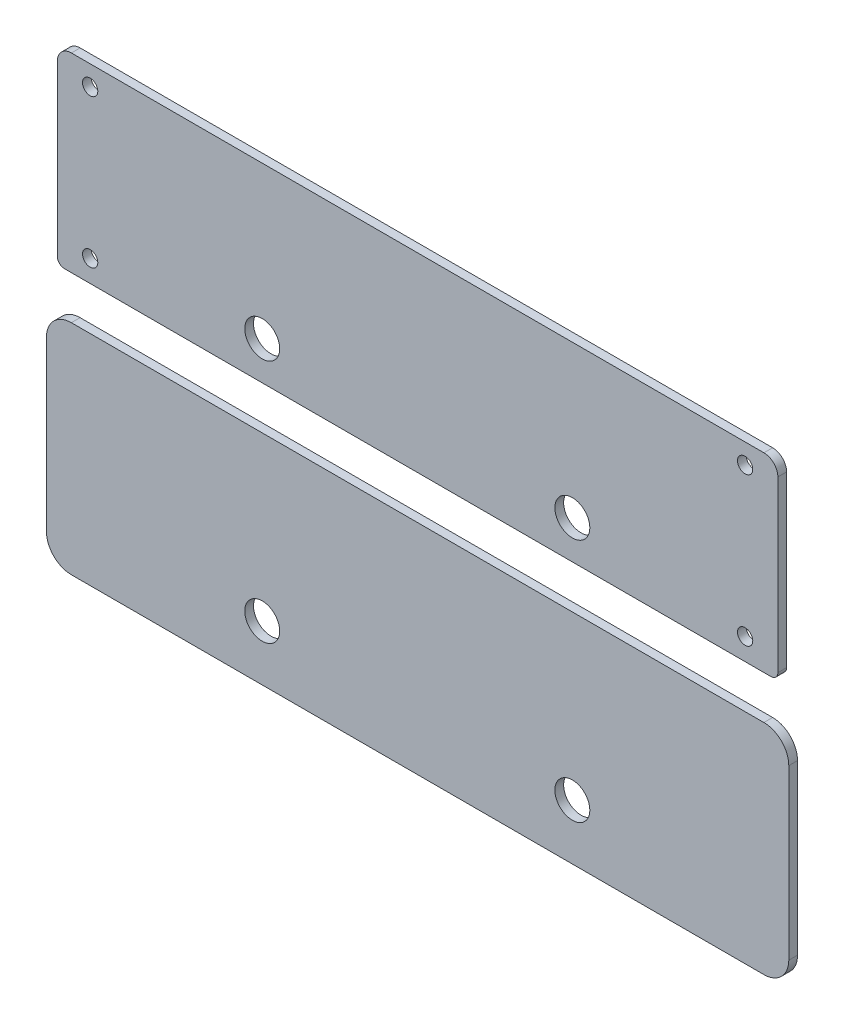
SolidWorks part; units mm, degrees
ref_plane "Front" through (0, 0, 0) normal (0, 0, 1) x (1, 0, 0)
ref_plane "Top" through (0, 0, 0) normal (0, 1, 0) x (1, 0, 0)
ref_plane "Right" through (0, 0, 0) normal (1, 0, 0) x (0, 0, -1)
sketch "Sketch1" plane through (0, 0, 0) normal (0, 0, 1) x (1, 0, 0)
  line L0 (-52.6295, -31.75) -> (-37.7705, -31.75)
  line L1 (37.5705, -31.75) -> (52.4295, -31.75)
  line L2 (-107.95, 24.511) -> (-107.95, -24.511)
  line L3 (-100.711, -31.75) -> (-52.6295, -31.75)
  line L4 (-37.7705, -31.75) -> (37.5705, -31.75)
  line L5 (52.4295, -31.75) -> (100.711, -31.75)
  line L6 (107.95, -24.511) -> (107.95, 24.511)
  line L7 (100.711, 31.75) -> (-100.711, 31.75)
  line L24 (100.711, 99.695) -> (-100.711, 99.695)
  line L25 (-104.775, 95.631) -> (-104.775, 50.345)
  line L31 (104.775, 50.345) -> (104.775, 95.631)
  line L32 (107.95, 46.609) -> (107.95, 95.631) [skipped]
  line L33 (84.775, 44.345) -> (-84.775, 44.345)
  line L34 (100.711, 102.87) -> (-100.711, 102.87) [skipped]
  line L35 (84.775, 44.345) -> (84.775, 50.345)
  line L36 (52.4295, 39.37) -> (100.711, 39.37) [skipped]
  line L37 (84.775, 50.345) -> (104.775, 50.345)
  line L38 (37.5705, 39.37) -> (52.4295, 39.37) [skipped]
  line L40 (-37.7705, 39.37) -> (37.5705, 39.37) [skipped]
  line L41 (0, 99.695) -> (0, 44.345) construction
  line L42 (-52.6295, 39.37) -> (-37.7705, 39.37) [skipped]
  line L43 (-84.775, 50.345) -> (-104.775, 50.345)
  line L44 (-100.711, 39.37) -> (-52.6295, 39.37) [skipped]
  line L45 (-84.775, 44.345) -> (-84.775, 50.345)
  line L46 (-107.95, 95.631) -> (-107.95, 46.609) [skipped]
  circle A0 centre (-45.2, -15.6502) radius 5.08
  circle A1 centre (45, -15.6502) radius 5.08
  arc A2 (-100.711, 31.75) -> (-107.95, 24.511) centre (-100.711, 24.511) ccw
  arc A3 (-107.95, -24.511) -> (-100.711, -31.75) centre (-100.711, -24.511) ccw
  arc A4 (100.711, -31.75) -> (107.95, -24.511) centre (100.711, -24.511) ccw
  arc A5 (107.95, 24.511) -> (100.711, 31.75) centre (100.711, 24.511) ccw
  circle A10 centre (-45.2, 55.4698) radius 5.08
  circle A11 centre (45, 55.4698) radius 5.08
  arc A18 (-100.711, 99.695) -> (-104.775, 95.631) centre (-100.711, 95.631) ccw
  arc A21 (104.775, 95.631) -> (100.711, 99.695) centre (100.711, 95.631) ccw
  arc A24 (107.95, 95.631) -> (100.711, 102.87) centre (100.711, 95.631) ccw [skipped]
  circle A25 centre (66.273, 2.3) radius 1.905 construction
  arc A26 (100.711, 39.37) -> (107.95, 46.609) centre (100.711, 46.609) ccw [skipped]
  arc A28 (-107.95, 46.609) -> (-100.711, 39.37) centre (-100.711, 46.609) ccw [skipped]
  circle A29 centre (35.023, 2.3) radius 1.905 construction
  arc A30 (-100.711, 102.87) -> (-107.95, 95.631) centre (-100.711, 95.631) ccw [skipped]
  circle A32 centre (50.648, 2.3) radius 12.065 construction
  circle A34 centre (12.5, 2.3) radius 9.25 construction
  dimension "D3" = 2
extrude "Boss-Extrude1" add sketch "Sketch1" along normal blind 2.54
sketch "Sketch2" [suppressed] plane through (0, 0, 2.54) normal (0, 0, 1) x (1, 0, 0)
  line L0 (-20.0864, 22.2366) -> (3.9841, 22.2366)
  line L1 (3.9841, 22.2366) -> (3.9841, 4.3544)
  line L2 (3.9841, 4.3544) -> (21.8236, 4.3544)
  line L3 (21.8236, 4.3544) -> (21.8236, -19.7588)
  line L4 (21.8236, -19.7588) -> (15.806, -19.7588)
  line L5 (15.806, -19.7588) -> (15.806, -1.7486)
  line L6 (15.806, -1.7486) -> (-1.9908, -1.7486)
  line L7 (-1.9908, -1.7486) -> (-1.9908, 16.2189)
  line L8 (-1.9908, 16.2189) -> (-20.0864, 16.2189)
  line L9 (-20.0864, 16.2189) -> (-20.0864, 22.2366)
  line L10 (-20.0864, 4.3544) -> (-14.0261, 4.3544)
  line L11 (-14.0261, 4.3544) -> (-14.0261, -13.6985)
  line L12 (-14.0261, -13.6985) -> (3.9841, -13.6985)
  line L13 (3.9841, -13.6985) -> (3.9841, -19.7588)
  line L14 (3.9841, -19.7588) -> (-20.0864, -19.7588)
  line L15 (-20.0864, -19.7588) -> (-20.0864, 4.3544)
extrude "Cut-Extrude1" [suppressed] cut sketch "Sketch2" against normal through all
sketch "Sketch3" [suppressed] plane through (0, 0, 2.54) normal (0, 0, 1) x (1, 0, 0)
  circle A0 centre (-45.2, 55.4698) radius 5.08 construction
  circle A1 centre (-45.2, 55.4698) radius 5.08
  circle A2 centre (45, 55.4698) radius 5.08 construction
  circle A3 centre (45, 55.4698) radius 5.08
extrude "Boss-Extrude2" [suppressed] add sketch "Sketch3" against normal through all
sketch "Sketch5" [suppressed] plane through (0, 0, 2.54) normal (0, 0, 1) x (1, 0, 0)
  line L0 (3.9841, -19.7588) -> (3.9841, -13.6985) construction
  line L1 (-20.0864, -19.7588) -> (3.9841, -19.7588) construction
  line L2 (-20.0864, 4.3544) -> (-20.0864, -19.7588) construction
  line L3 (-14.0261, 4.3544) -> (-20.0864, 4.3544) construction
  line L4 (-14.0261, -13.6985) -> (-14.0261, 4.3544) construction
  line L5 (3.9841, -13.6985) -> (-14.0261, -13.6985) construction
  line L6 (3.9841, -19.7588) -> (3.9841, -13.6985)
  line L7 (-20.0864, -19.7588) -> (3.9841, -19.7588)
  line L8 (-20.0864, 4.3544) -> (-20.0864, -19.7588)
  line L9 (-14.0261, 4.3544) -> (-20.0864, 4.3544)
  line L10 (-14.0261, -13.6985) -> (-14.0261, 4.3544)
  line L11 (3.9841, -13.6985) -> (-14.0261, -13.6985)
  line L12 (-1.9908, -1.7486) -> (15.806, -1.7486) construction
  line L13 (-1.9908, 16.2189) -> (-1.9908, -1.7486) construction
  line L14 (-20.0864, 16.2189) -> (-1.9908, 16.2189) construction
  line L15 (-20.0864, 22.2366) -> (-20.0864, 16.2189) construction
  line L16 (3.9841, 22.2366) -> (-20.0864, 22.2366) construction
  line L17 (3.9841, 4.3544) -> (3.9841, 22.2366) construction
  line L18 (21.8236, 4.3544) -> (3.9841, 4.3544) construction
  line L19 (21.8236, -19.7588) -> (21.8236, 4.3544) construction
  line L20 (15.806, -19.7588) -> (21.8236, -19.7588) construction
  line L21 (15.806, -1.7486) -> (15.806, -19.7588) construction
  line L22 (-1.9908, -1.7486) -> (15.806, -1.7486)
  line L23 (-1.9908, 16.2189) -> (-1.9908, -1.7486)
  line L24 (-20.0864, 16.2189) -> (-1.9908, 16.2189)
  line L25 (-20.0864, 22.2366) -> (-20.0864, 16.2189)
  line L26 (3.9841, 22.2366) -> (-20.0864, 22.2366)
  line L27 (3.9841, 4.3544) -> (3.9841, 22.2366)
  line L28 (21.8236, 4.3544) -> (3.9841, 4.3544)
  line L29 (21.8236, -19.7588) -> (21.8236, 4.3544)
  line L30 (15.806, -19.7588) -> (21.8236, -19.7588)
  line L31 (15.806, -1.7486) -> (15.806, -19.7588)
  circle A0 centre (-45.2, -15.6502) radius 5.08 construction
  circle A1 centre (-45.2, -15.6502) radius 5.08
  circle A2 centre (45, -15.6502) radius 5.08 construction
  circle A3 centre (45, -15.6502) radius 5.08
extrude "Boss-Extrude3" [suppressed] add sketch "Sketch5" against normal through all
sketch "Sketch6" [suppressed] plane through (0, 0, 2.54) normal (0, 0, 1) x (1, 0, 0)
  circle A0 centre (12.5, 2.3) radius 9.25 construction
  circle A1 centre (12.5, 2.3) radius 9.25
  circle A2 centre (35.023, 2.3) radius 1.905 construction
  circle A3 centre (35.023, 2.3) radius 1.905
  circle A4 centre (50.648, 2.3) radius 12.065 construction
  circle A5 centre (50.648, 2.3) radius 12.065
  circle A6 centre (66.273, 2.3) radius 1.905 construction
  circle A7 centre (66.273, 2.3) radius 1.905
extrude "Cut-Extrude2" [suppressed] cut sketch "Sketch6" against normal through all
sketch "Sketch7" [suppressed] plane through (0, 0, 0) normal (0, 0, -1) x (-1, 0, 0)
  line L1 (-74.2733, 90.9286) -> (5.6813, 90.9286)
  line L2 (-74.2733, 90.9286) -> (-74.2733, 56.2734)
  line L3 (-74.2733, 56.2734) -> (5.6813, 56.2734)
  line L4 (5.6813, 90.9286) -> (5.6813, 56.2734)
extrude "Cut-Extrude3" [suppressed] cut sketch "Sketch7" against normal through all
sketch "Sketch8" [suppressed] plane through (0, 0, 2.54) normal (0, 0, 1) x (1, 0, 0)
  line L0 (0, 31.75) -> (0, 1.16) construction
  line L1 (95.25, -20.43) -> (-95.25, -20.43) construction
  line L2 (95.25, -20.43) -> (95.25, 22.75) construction
  line L3 (95.25, 22.75) -> (-95.25, 22.75) construction
  line L4 (-95.25, -20.43) -> (-95.25, 22.75) construction
  line L5 (95.25, -20.43) -> (-95.25, 22.75) construction
  line L6 (95.25, 22.75) -> (-95.25, -20.43) construction
  line L7 (100.711, 31.75) -> (-100.711, 31.75) construction
  circle A0 centre (-95.25, 22.75) radius 2.2225
  circle A1 centre (-95.25, -20.43) radius 2.2225
  circle A2 centre (95.25, -20.43) radius 2.2225
  circle A3 centre (95.25, 22.75) radius 2.2225
  dimension "D1" = 4.445
  dimension "D2" = 43.18
  dimension "D3" = 190.5
  dimension "D4" = 9
extrude "Cut-Extrude4" [suppressed] cut sketch "Sketch8" against normal through all
sketch "Sketch9" plane through (0, 0, 2.54) normal (0, 0, 1) x (1, 0, 0)
  line L0 (-104.775, 50.345) -> (-84.775, 50.345)
  line L1 (-84.775, 50.345) -> (-84.775, 44.345)
  line L2 (-84.775, 44.345) -> (-104.775, 44.345)
  line L3 (-104.775, 44.345) -> (-104.775, 50.345)
  line L4 (84.775, 50.345) -> (104.775, 50.345)
  line L5 (104.775, 50.345) -> (104.775, 44.345)
  line L6 (104.775, 44.345) -> (84.775, 44.345)
  line L7 (84.775, 50.345) -> (84.775, 44.345)
extrude "Boss-Extrude4" add sketch "Sketch9" against normal up to surface (2.54 mm away) up to face at (0, 68.2405, 0)
fillet "Fillet1" radius 2 2 edges at (104.775, 44.345, 1.27) (-104.775, 44.345, 1.27)
sketch "Sketch10" plane through (0, 0, 2.54) normal (0, 0, 1) x (1, 0, 0)
  circle A1 centre (95.25, 93.87) radius 2.2225
  circle A2 centre (95.25, 93.87) radius 2.2225
  circle A3 centre (95.25, 50.69) radius 2.2225
  circle A4 centre (95.25, 50.69) radius 2.2225
  circle A5 centre (-95.25, 50.69) radius 2.2225
  circle A6 centre (-95.25, 50.69) radius 2.2225
  circle A7 centre (-95.25, 93.87) radius 2.2225
  circle A8 centre (-95.25, 93.87) radius 2.2225
  dimension "D1" = 0
  dimension "D2" = 0
  dimension "D3" = 0
  dimension "D4" = 0
extrude "Cut-Extrude5" cut sketch "Sketch10" against normal through all
sketch "Sketch12" [suppressed] plane through (0, 0, 0) normal (0, 0, -1) x (-1, 0, 0)
  line L1 (104.775, 50.345) -> (84.775, 50.345)
  line L2 (104.775, 50.345) -> (104.775, 44.345)
  line L3 (104.775, 44.345) -> (84.775, 44.345)
  line L4 (84.775, 50.345) -> (84.775, 44.345)
  line L5 (-104.775, 50.345) -> (-84.775, 50.345)
  line L6 (-104.775, 50.345) -> (-104.775, 44.345)
  line L7 (-104.775, 44.345) -> (-84.775, 44.345)
  line L8 (-84.775, 50.345) -> (-84.775, 44.345)
extrude "Boss-Extrude5" [suppressed] add sketch "Sketch12" against normal up to surface (2.54 mm away)
fillet "Fillet2" [suppressed] radius 2.5
sketch "Sketch11" [suppressed] plane through (0, 0, 2.54) normal (0, 0, 1) x (1, 0, 0)
  circle A1 centre (95.25, 93.87) radius 2.2225
  circle A2 centre (95.25, 93.87) radius 2.2225
  circle A3 centre (95.25, 50.69) radius 2.2225
  circle A4 centre (95.25, 50.69) radius 2.2225
  circle A5 centre (-95.25, 50.69) radius 2.2225
  circle A6 centre (-95.25, 50.69) radius 2.2225
  circle A7 centre (-95.25, 93.87) radius 2.2225
  circle A8 centre (-95.25, 93.87) radius 2.2225
  dimension "D1" = 0
  dimension "D2" = 0
  dimension "D3" = 0
  dimension "D4" = 0
extrude "Cut-Extrude6" [suppressed] cut sketch "Sketch11" against normal through all
sketch "Sketch13" [suppressed] plane through (0, 0, 2.54) normal (0, 0, 1) x (1, 0, 0)
  circle A1 centre (-95.25, 22.75) radius 2.2225
  circle A2 centre (-95.25, 22.75) radius 2.2225
  circle A3 centre (-95.25, -20.43) radius 2.2225
  circle A4 centre (-95.25, -20.43) radius 2.2225
  circle A5 centre (95.25, -20.43) radius 2.2225
  circle A6 centre (95.25, -20.43) radius 2.2225
  circle A7 centre (95.25, 22.75) radius 2.2225
  circle A8 centre (95.25, 22.75) radius 2.2225
  dimension "D1" = 0
  dimension "D2" = 0
  dimension "D3" = 0
  dimension "D4" = 0
extrude "Cut-Extrude7" [suppressed] cut sketch "Sketch13" against normal through all
